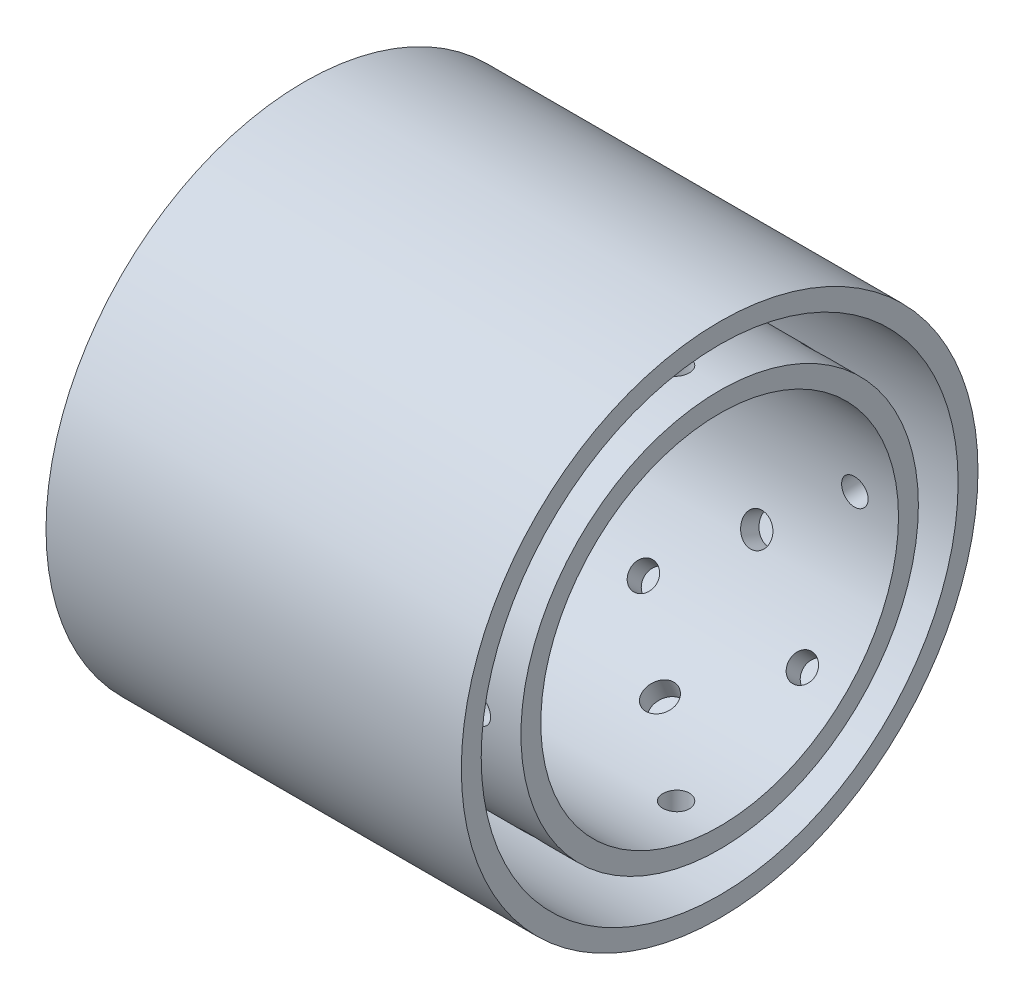
SolidWorks part; units mm, degrees
ref_plane "Front Plane" through (0, 0, 0) normal (0, 0, 1) x (1, 0, 0)
ref_plane "Top Plane" through (0, 0, 0) normal (0, 1, 0) x (1, 0, 0)
ref_plane "Right Plane" through (0, 0, 0) normal (1, 0, 0) x (0, 0, -1)
sketch "Sketch1" plane through (0, 0, 0) normal (1, 0, 0) x (0, 0, -1)
  circle A0 centre (0, 0) radius 100
  circle A1 centre (0, 0) radius 90
  dimension "D1" = 10
extrude "Boss-Extrude1" add sketch "Sketch1" along normal blind 209
sketch "Sketch2" plane through (0, 0, 0) normal (0, 1, 0) x (1, 0, 0)
  circle A0 centre (27.0477, 0) radius 6.6719
  circle A2 centre (107.0477, 0) radius 6.6719
  circle A4 centre (187.0477, 0) radius 6.6719
  circle A5 centre (67.0477, 0) radius 6.6719 [skipped]
  circle A6 centre (147.0477, 0) radius 6.6719 [skipped]
  dimension "D1" = 5
extrude "Cut-Extrude1" cut sketch "Sketch2" against normal blind 209
pattern_circular "CirPattern1" count 8 over 360 about axis through (0, 0, 0) along (1, 0, 0) of "Cut-Extrude1"
ref_plane "Plane1" through (0, 0, 0) normal (0, -0.7071, 0.7071) x (1, 0, 0)
ref_plane "Plane2" through (0, 0, 0) normal (0, -0.9239, -0.3827) x (-1, 0, 0)
sketch "Sketch3" plane through (0, 0, 0) normal (0, -0.9239, -0.3827) x (-1, 0, 0)
  circle A0 centre (-64.5532, 0) radius 7.5803
  circle A1 centre (-144.5532, 0) radius 7.5803
  dimension "D1" = 2
extrude "Cut-Extrude2" cut sketch "Sketch3" against normal blind 209
pattern_circular "CirPattern2" count 8 over 360 about axis through (0, 0, 0) along (1, 0, 0) of "Cut-Extrude2"
sketch "Sketch4" plane through (0, 0, 0) normal (-1, 0, 0) x (0, 0, 1)
  circle A0 centre (0, 0) radius 120
  circle A1 centre (0, 0) radius 130
  circle A2 centre (0, 0) radius 100 construction
  dimension "D1" = 10
  dimension "D2" = 20
extrude "Boss-Extrude3" add sketch "Sketch4" against normal blind 209 separate body
